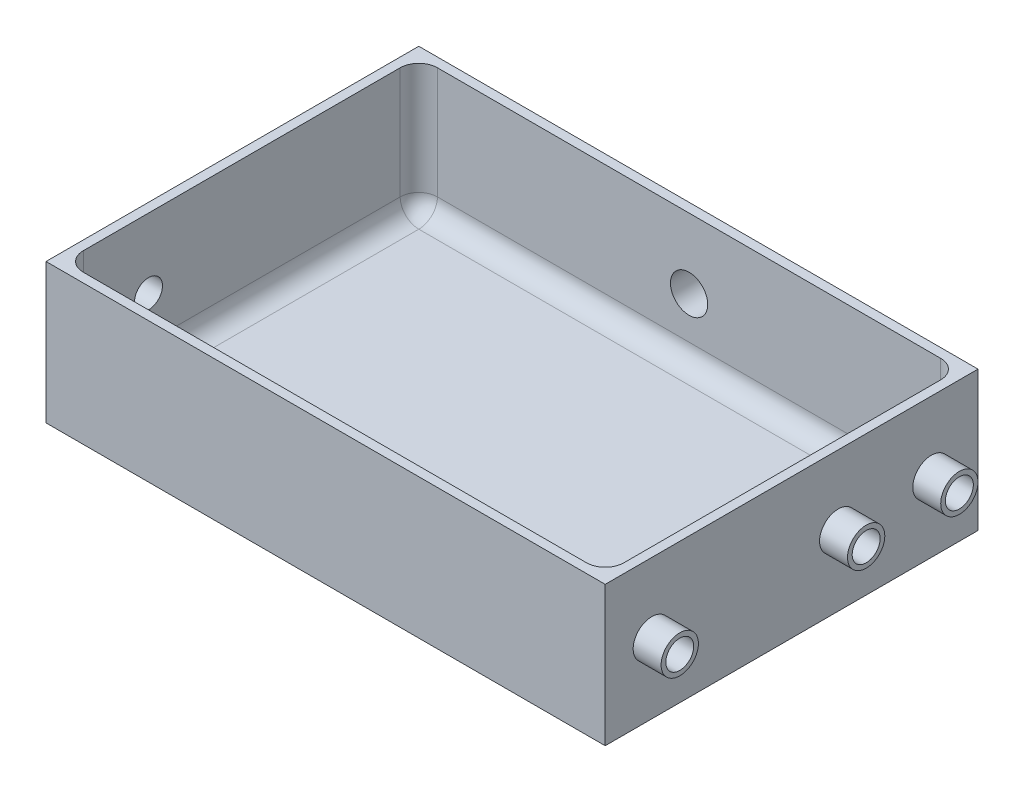
SolidWorks part; units mm, degrees
ref_plane "Front Plane" through (0, 0, 0) normal (0, 0, 1) x (1, 0, 0)
ref_plane "Top Plane" through (0, 0, 0) normal (0, 1, 0) x (1, 0, 0)
ref_plane "Right Plane" through (0, 0, 0) normal (1, 0, 0) x (0, 0, -1)
sketch "Sketch1" plane through (0, 0, 0) normal (0, 1, 0) x (1, 0, 0)
  line L1 (150, 100) -> (-150, 100)
  line L2 (150, 100) -> (150, -100)
  line L3 (150, -100) -> (-150, -100)
  line L4 (-150, 100) -> (-150, -100)
  line L5 (150, 100) -> (-150, -100) construction
  line L6 (150, -100) -> (-150, 100) construction
  point P0 (0, 0)
  dimension "D1" = 200
  dimension "D2" = 300
extrude "Boss-Extrude1" add sketch "Sketch1" along normal mid plane 75
shell "Shell1" thickness 5
fillet "Fillet1" radius 10 8 edges at (145, 2.5, -95) (145, -32.5, 0) (145, 2.5, 95) (0, -32.5, 95) (-145, 2.5, 95) (-145, -32.5, 0) (-145, 2.5, -95) (0, -32.5, -95)
sketch "Sketch2" plane through (150, 0, 0) normal (1, 0, 0) x (0, 0, -1)
  line L0 (-89.3275, 0) -> (90.5373, 0) construction
  line L1 (0, 54.645) -> (0, -60.4926) construction
  circle A0 centre (75, 0) radius 7.5
  circle A1 centre (25, 0) radius 7.5
  circle A2 centre (-75, 0) radius 7.5
  dimension "D2" = 15
  dimension "D5" = 15
  dimension "D3" = 25
  dimension "D4" = 50
extrude "Cut-Extrude1" cut sketch "Sketch2" against normal blind 5
sketch "Sketch3" plane through (-145, 0, 0) normal (1, 0, 0) x (0, 0, -1)
  circle A0 centre (-50, 0) radius 7.5
  dimension "D1" = 50
  dimension "D2" = 15
extrude "Cut-Extrude2" cut sketch "Sketch3" against normal blind 5
sketch "Sketch4" plane through (0, 0, -95) normal (0, 0, 1) x (1, 0, 0)
  circle A0 centre (0, 0) radius 10
  dimension "D1" = 20
extrude "Cut-Extrude3" cut sketch "Sketch4" against normal blind 5
sketch "Sketch5" plane through (150, 0, 0) normal (1, 0, 0) x (0, 0, -1)
  circle A0 centre (-75, 0) radius 10
  circle A1 centre (-75, 0) radius 7.5
  circle A2 centre (-75, 0) radius 7.5 construction
  circle A3 centre (25, 0) radius 10
  circle A4 centre (75, 0) radius 10
  circle A5 centre (25, 0) radius 7.5
  circle A6 centre (75, 0) radius 7.5
  dimension "D1" = 20
  dimension "D2" = 20
  dimension "D3" = 15
  dimension "D4" = 15
  dimension "D5" = 20
extrude "Boss-Extrude2" add sketch "Sketch5" along normal blind 15
sketch "Sketch6" plane through (-150, 0, 0) normal (-1, 0, 0) x (0, 0, 1)
  line L4 (-100, -37.5) -> (100, -37.5)
  line L5 (100, -37.5) -> (100, 37.5)
  line L6 (100, 37.5) -> (-100, 37.5)
  line L7 (-100, 37.5) -> (-100, -37.5)
  line L8 (-100, -37.5) -> (100, -37.5)
  line L9 (100, -37.5) -> (100, 37.5)
  line L10 (100, 37.5) -> (-100, 37.5)
  line L11 (-100, 37.5) -> (-100, -37.5)
  circle A0 centre (50, 0) radius 10
  circle A1 centre (50, 0) radius 7.5
  dimension "D1" = 0
  dimension "D2" = 20
  dimension "D3" = 15
extrude "Boss-Extrude3" add sketch "Sketch6" along normal blind 15 contours A1 | A0
sketch "Sketch7" plane through (0, 0, -100) normal (0, 0, -1) x (-1, 0, 0)
  circle A0 centre (0, 0) radius 10
  circle A1 centre (0, 0) radius 12.5
  dimension "D1" = 20
  dimension "D2" = 25
extrude "Boss-Extrude4" add sketch "Sketch7" along normal blind 15
